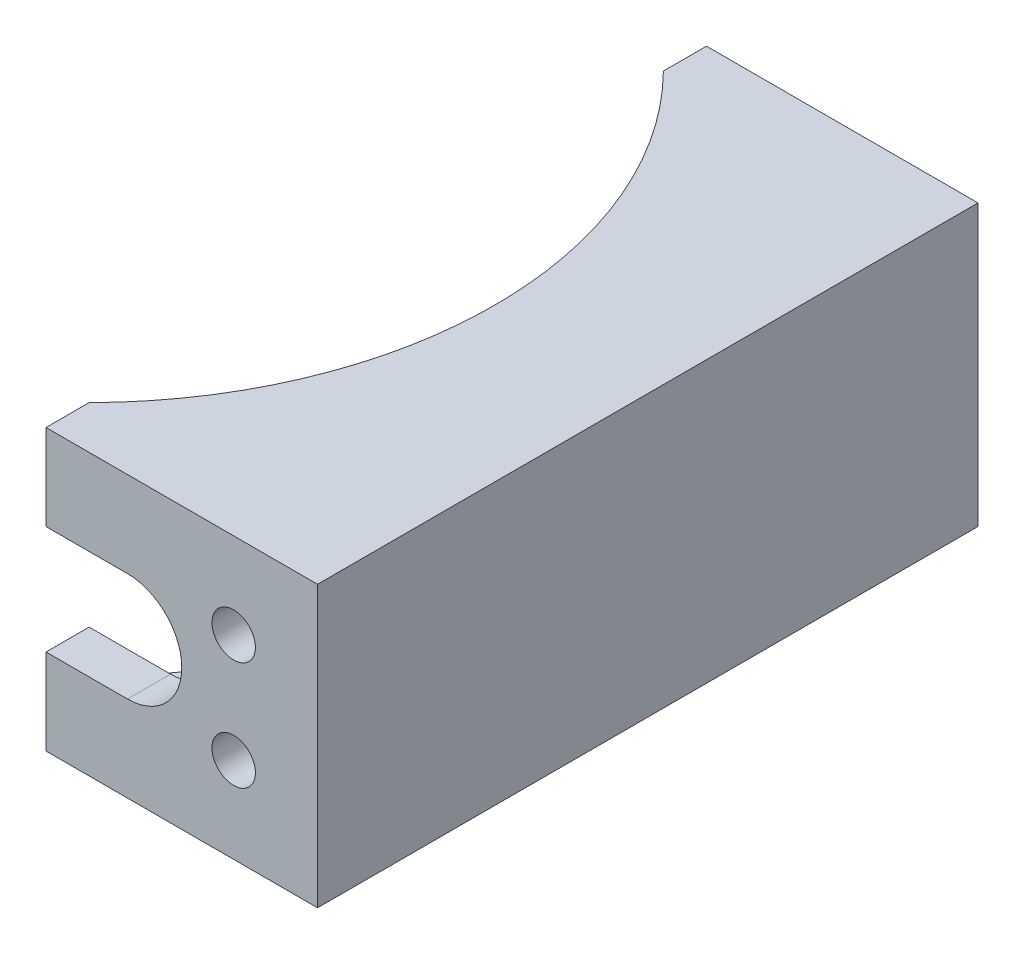
SolidWorks part; units mm, degrees
ref_plane "Front Plane" through (0, 0, 0) normal (0, 0, 1) x (1, 0, 0)
ref_plane "Top Plane" through (0, 0, 0) normal (0, 1, 0) x (1, 0, 0)
ref_plane "Right Plane" through (0, 0, 0) normal (1, 0, 0) x (0, 0, -1)
sketch "Sketch1" plane through (0, 0, 0) normal (0, 1, 0) x (1, 0, 0)
  line L0 (0, 0) -> (20, 0)
  line L1 (20, 0) -> (20, -42.3)
  line L2 (20, -42.3) -> (0, -42.3)
  arc A0 (0, -42.3) -> (0, 0) centre (-21.2762, -21.15) ccw
  dimension "D3" = 30
  dimension "D1" = 20
  dimension "D2" = 42.3
extrude "Boss-Extrude1" add sketch "Sketch1" along normal blind 3.175
sketch "Sketch2" plane through (0, 3.175, 0) normal (0, 1, 0) x (1, 0, 0)
  line L0 (0, -42.3) -> (20, -42.3) construction
  line L1 (20, 0) -> (16.825, 0)
  line L2 (20, 0) -> (20, -42.3)
  line L3 (20, -42.3) -> (16.825, -42.3)
  line L4 (16.825, 0) -> (16.825, -42.3)
  dimension "D1" = 3.175
extrude "Boss-Extrude2" add sketch "Sketch2" along normal blind 14.29
ref_plane "Plane1" through (0, 10.32, 0) normal (0, 1, 0) x (1, 0, 0)
mirror "Mirror1" about plane through (0, 10.32, 0) normal (0, 1, 0) of "Boss-Extrude1"
sketch "Sketch3" plane through (0, 0, 0) normal (0, 0, -1) x (-1, 0, 0)
  line L0 (-20, 20.64) -> (0, 20.64) construction
  line L1 (-20, 0) -> (0, 0)
  line L2 (-20, 0) -> (-20, 20.64)
  line L3 (-20, 20.64) -> (0, 20.64)
  line L4 (0, 0) -> (0, 6.32)
  line L5 (-13.825, 6.32) -> (-13.825, 14.32) construction
  line L6 (9.2538, 10.32) -> (-9.2538, 10.32) construction
  line L7 (-16.825, 17.465) -> (-16.825, 3.175) construction
  line L8 (0, 3.175) -> (0, 0) construction
  line L9 (-6, 6.32) -> (0, 6.32)
  line L10 (-6, 14.32) -> (0, 14.32)
  line L11 (0, 14.32) -> (0, 20.64)
  circle A0 centre (-13.825, 6.32) radius 1.6
  circle A1 centre (-13.825, 14.32) radius 1.6
  arc A2 (-6, 14.32) -> (-6, 6.32) centre (-6, 10.32) ccw
  point P11 (-13.825, 10.32)
  dimension "D1" = 3.2
  dimension "D4" = 8
  dimension "D2" = 8
  dimension "D3" = 3
  dimension "D5" = 6
extrude "Boss-Extrude3" add sketch "Sketch3" along normal blind 3.175
ref_plane "Plane2" through (0, 0, 21.15) normal (0, 0, 1) x (1, 0, 0)
mirror "Mirror2" about plane through (0, 0, 21.15) normal (0, 0, 1) of "Boss-Extrude3"
